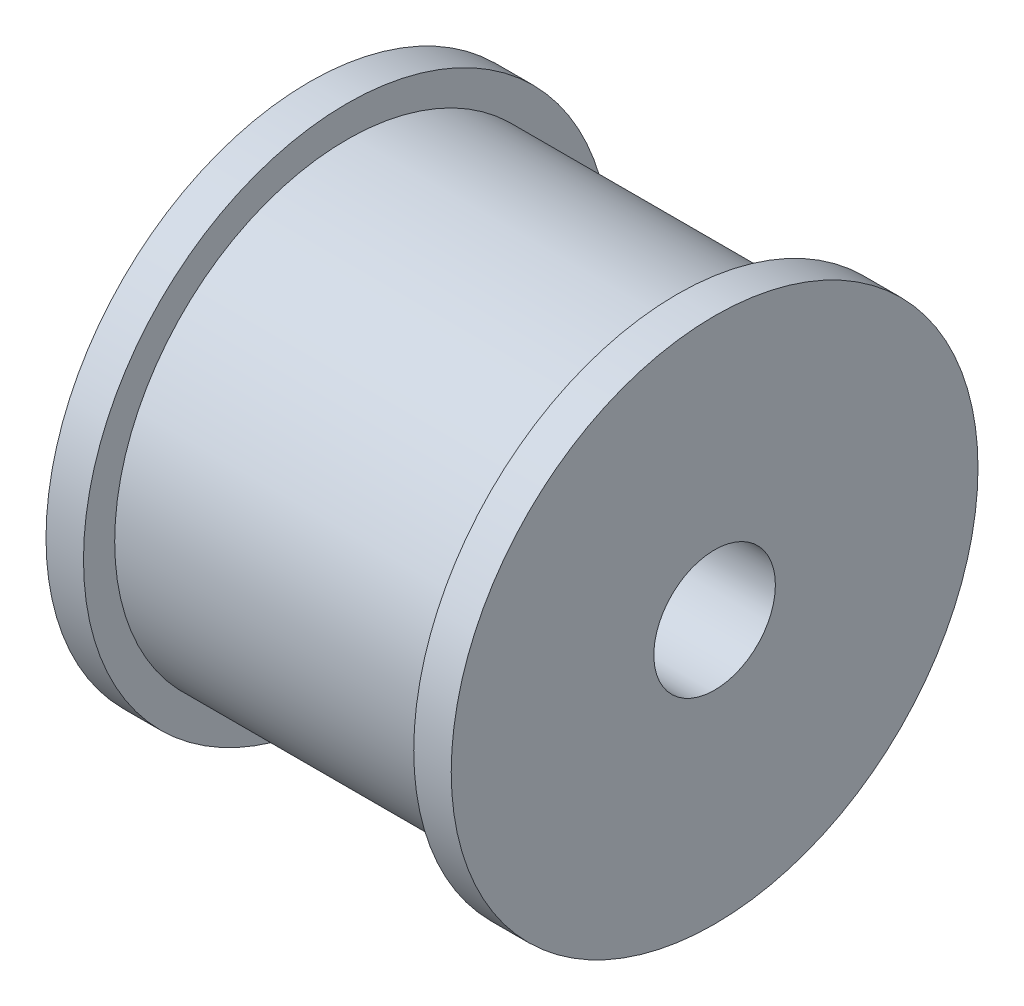
SolidWorks part; units mm, degrees
ref_plane "Front Plane" through (0, 0, 0) normal (0, 0, 1) x (1, 0, 0)
ref_plane "Top Plane" through (0, 0, 0) normal (0, 1, 0) x (1, 0, 0)
ref_plane "Right Plane" through (0, 0, 0) normal (1, 0, 0) x (0, 0, -1)
sketch "Sketch1" plane through (0, 0, 0) normal (0, 1, 0) x (1, 0, 0)
  line L0 (0, -11.46) -> (-8.15, -11.46)
  line L1 (-8.15, -13) -> (-10, -13)
  line L2 (-10, -13) -> (-10, 0)
  line L3 (10, 0) -> (10, -13)
  line L4 (10, -13) -> (8.15, -13)
  line L5 (8.15, -13) -> (8.15, -11.46)
  line L6 (8.15, -11.46) -> (0, -11.46)
  line L7 (-8.15, -11.46) -> (-8.15, -13)
  line L8 (-10, 0) -> (10, 0) construction
  line L9 (10, 0) -> (-10, 0)
  dimension "D1" = 13
  dimension "D2" = 1.85
  dimension "D3" = 10
  dimension "D4" = 11.46
  dimension "D5" = 10
  dimension "D6" = 1.85
revolve "Revolve1" add sketch "Sketch1" angle 360 about L8
hole_wizard "Ø6.0 (6) Diameter Hole2" positions "Sketch8" profile "Sketch7" hole size "Ø6.0" standard "ANSI Metric"
sketch "Sketch8" plane through (10, 0, 0) normal (1, 0, 0) x (0, 0, -1)
  point P0 (0, 0)
sketch "Sketch7" plane through (10, 0, 0) normal (0, 1, 0) x (0, 0, -1)
  line L0 (0, 0) -> (0, 25.8026)
  line L1 (0, 25.8026) -> (3, 24)
  line L2 (3, 24) -> (3, 0)
  line L5 (3, 0) -> (0, 0)
  line L10 (0, 25.8026) -> (-3, 24) construction
  line L11 (0, -6.35) -> (0, 107.95) construction
  dimension "Hole Dia." = 6
  dimension "Hole Depth" = 24
  dimension "Drill Angle" = 118
